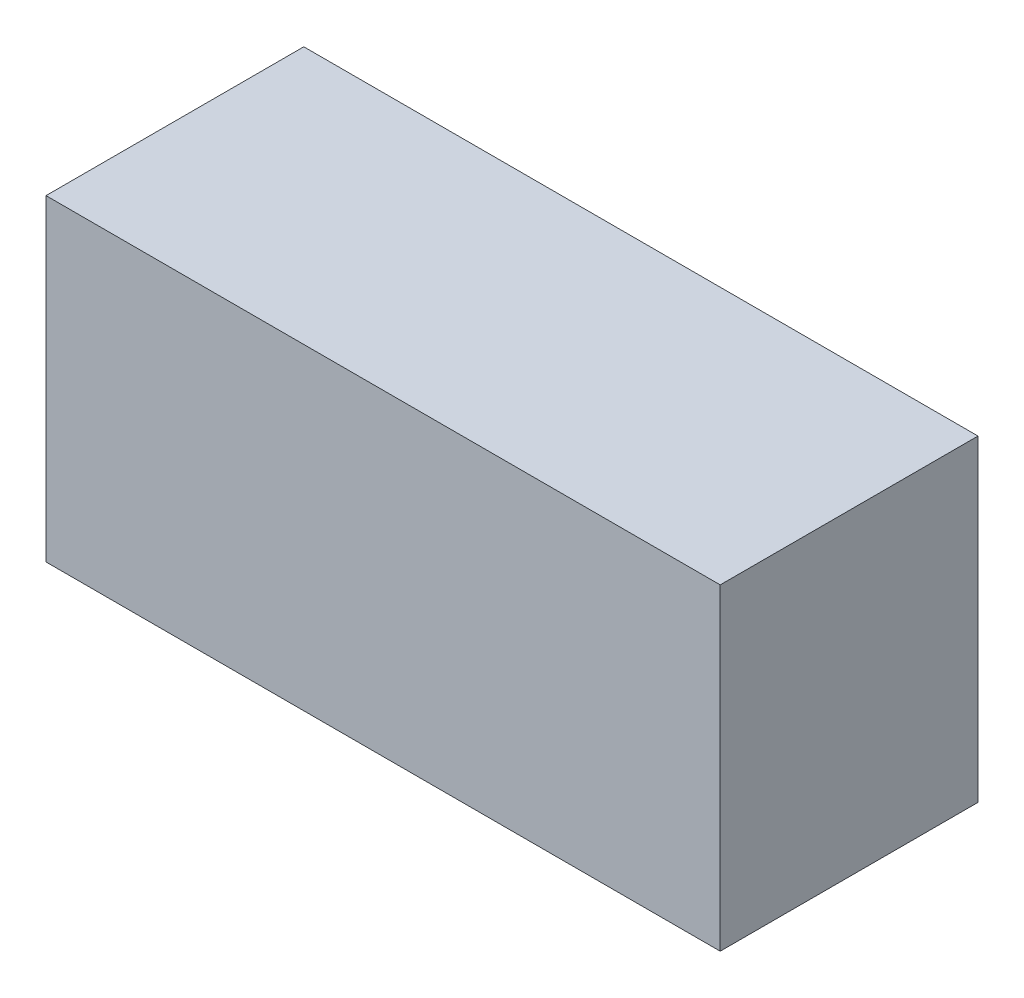
SolidWorks part; units mm, degrees
ref_plane "Front Plane" through (0, 0, 0) normal (0, 0, 1) x (1, 0, 0)
ref_plane "Top Plane" through (0, 0, 0) normal (0, 1, 0) x (1, 0, 0)
ref_plane "Right Plane" through (0, 0, 0) normal (1, 0, 0) x (0, 0, -1)
sketch "Sketch1" plane through (0, 0, 0) normal (0, 0, 1) x (1, 0, 0)
  line L0 (1.875, 0.4) -> (1.875, -0.4)
  line L1 (1.875, -0.4) -> (0.175, -0.4)
  line L2 (0.175, -0.4) -> (0.175, 0.4)
  line L3 (0.175, 0.4) -> (1.875, 0.4)
extrude "Component_Outline" add sketch "Sketch1" along normal blind 0.65 separate body
sketch3d "3DSketch1"
  line L0 (0, 0, 0) -> (1, 0, 0)
  line L1 (0, 0, 0) -> (0, 1, 0)
  line L2 (0, 0, 0) -> (0, 0, 1)
  point P0 (0, 0, 0)
